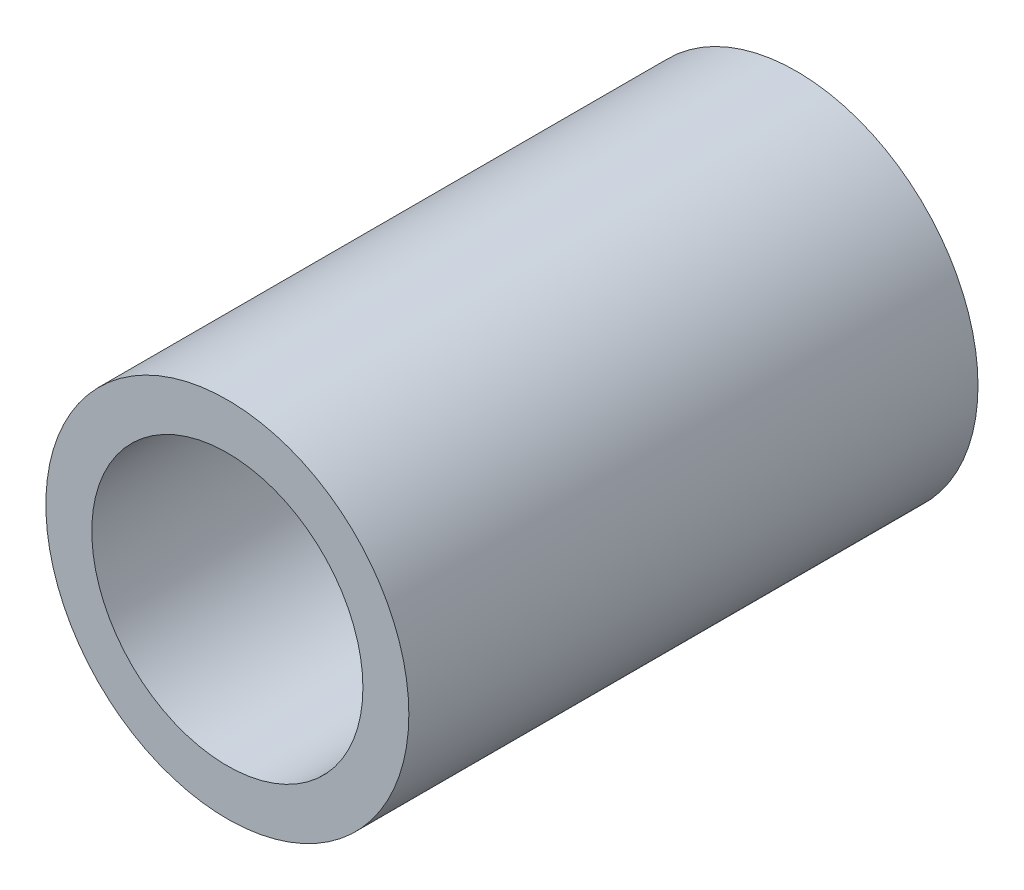
SolidWorks part; units mm, degrees
ref_plane "Front Plane" through (0, 0, 0) normal (0, 0, 1) x (1, 0, 0)
ref_plane "Top Plane" through (0, 0, 0) normal (0, 1, 0) x (1, 0, 0)
ref_plane "Right Plane" through (0, 0, 0) normal (1, 0, 0) x (0, 0, -1)
sketch "S01 - Installed brass envelope - simplified threads" plane through (0, 0, 0) normal (0, 0, 1) x (1, 0, 0)
  circle A0 centre (0, 0) radius 4.05
  circle A1 centre (0, 0) radius 3.025
extrude "01 - Installed brass envelope - simplified threads" add sketch "S01 - Installed brass envelope - simplified threads" along normal blind 12.7
